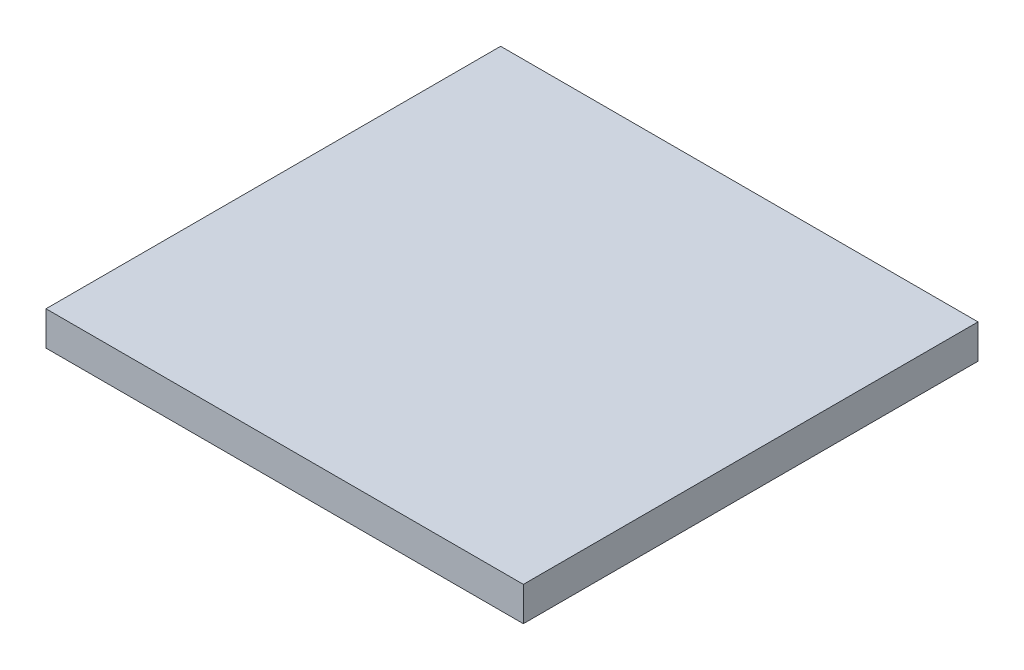
SolidWorks part; units mm, degrees
ref_plane "Front Plane" through (0, 0, 0) normal (0, 0, 1) x (1, 0, 0)
ref_plane "Top Plane" through (0, 0, 0) normal (0, 1, 0) x (1, 0, 0)
ref_plane "Right Plane" through (0, 0, 0) normal (1, 0, 0) x (0, 0, -1)
sketch "Sketch1" plane through (0, 0, 0) normal (0, 1, 0) x (1, 0, 0)
  line L1 (-133.35, 127) -> (133.35, 127)
  line L2 (-133.35, 127) -> (-133.35, -127)
  line L3 (-133.35, -127) -> (133.35, -127)
  line L4 (133.35, 127) -> (133.35, -127)
  line L5 (-133.35, 127) -> (133.35, -127) construction
  line L6 (-133.35, -127) -> (133.35, 127) construction
  point P0 (0, 0)
  dimension "D1" = 266.7
  dimension "D2" = 254
extrude "Boss-Extrude1" add sketch "Sketch1" along normal mid plane 19.05
